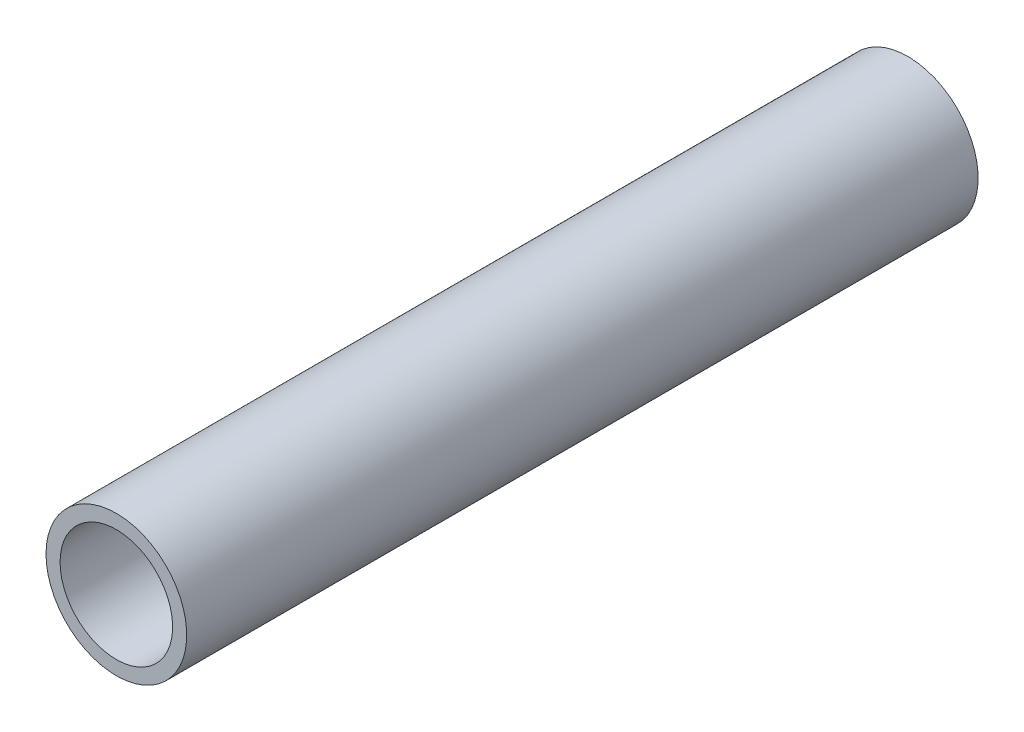
SolidWorks part; units mm, degrees
material "304不锈钢"
ref_plane "前视基准面" through (0, 0, 0) normal (0, 0, 1) x (1, 0, 0)
ref_plane "上视基准面" through (0, 0, 0) normal (0, 1, 0) x (1, 0, 0)
ref_plane "右视基准面" through (0, 0, 0) normal (1, 0, 0) x (0, 0, -1)
sketch "草图1" plane through (0, 0, 0) normal (0, 0, 1) x (1, 0, 0)
  circle A0 centre (0, 0) radius 1.6
  circle A1 centre (0, 0) radius 2
  dimension "D1" = 3.2
  dimension "D2" = 4
extrude "凸台-拉伸1" add sketch "草图1" along normal blind 22.5
